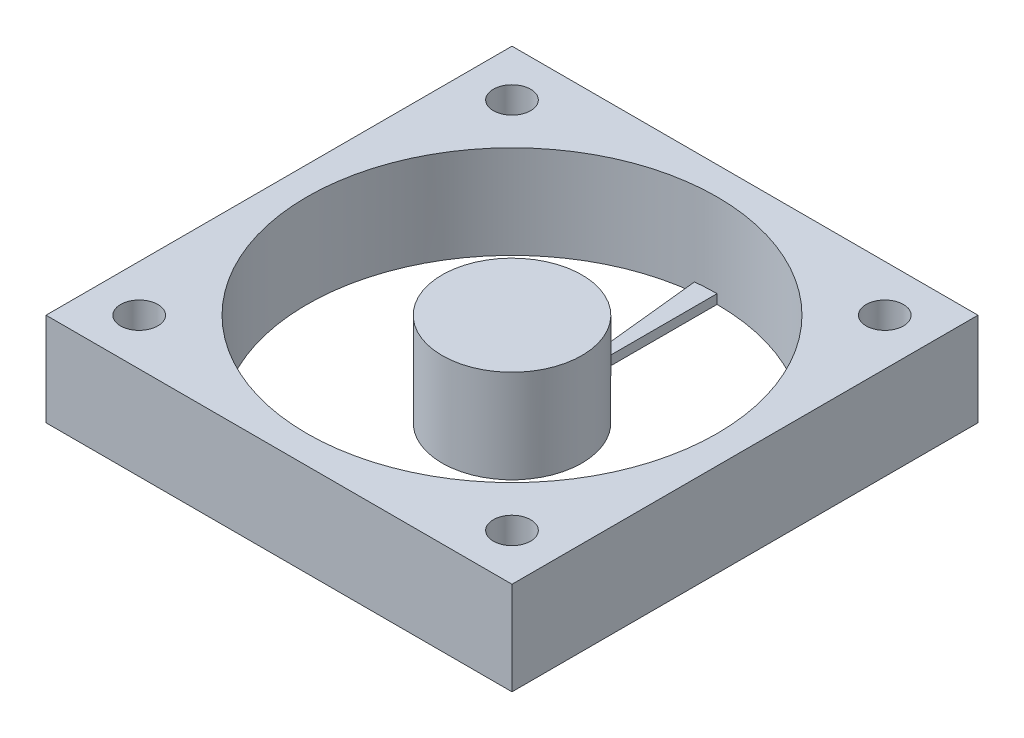
SolidWorks part; units mm, degrees
ref_plane "前视基准面" through (0, 0, 0) normal (0, 0, 1) x (1, 0, 0)
ref_plane "上视基准面" through (0, 0, 0) normal (0, 1, 0) x (1, 0, 0)
ref_plane "右视基准面" through (0, 0, 0) normal (1, 0, 0) x (0, 0, -1)
sketch "草图1" plane through (0, 0, 0) normal (0, 1, 0) x (1, 0, 0)
  line L0 (45, 5) -> (5, 45) construction
  line L1 (0, 0) -> (50, 0)
  line L2 (0, 0) -> (0, 50)
  line L3 (0, 50) -> (50, 50)
  line L4 (50, 0) -> (50, 50)
  line L5 (25, 25) -> (25, 50) construction
  line L6 (25, 25) -> (0, 25) construction
  circle A0 centre (5, 45) radius 2
  circle A1 centre (45, 45) radius 2
  circle A2 centre (45, 5) radius 2
  circle A3 centre (5, 5) radius 2
  point P15 (0, 0)
  dimension "D3" = 40
  dimension "D4" = 4
  dimension "D1" = 50
  dimension "D2" = 40
extrude "凸台-拉伸1" add sketch "草图1" along normal blind 10
sketch "草图2" plane through (0, 10, 0) normal (0, 1, 0) x (1, 0, 0)
  line L0 (25, 50) -> (25, 25) construction
  line L1 (50, 50) -> (0, 50) construction
  line L2 (25, 25) -> (0, 25) construction
  line L3 (0, 50) -> (0, 0) construction
  circle A0 centre (25, 25) radius 7.5
  circle A1 centre (25, 25) radius 22
  point P7 (0, 0)
  point P11 (25, 24.1234)
  dimension "D1" = 44
  dimension "D2" = 15
extrude "切除-拉伸2" cut sketch "草图2" against normal blind 9
sketch "草图3" plane through (0, 1, 0) normal (0, 1, 0) x (1, 0, 0)
  line L0 (24.216, 32.4589) -> (22.7004, 46.8795)
  line L1 (25, 32.5) -> (25, 47)
  circle A0 centre (25, 25) radius 7.5 construction
  circle A1 centre (25, 25) radius 7.5 construction
  arc A2 (25, 32.5) -> (24.216, 32.4589) centre (25, 25) cw
  arc A3 (22.7004, 46.8795) -> (25, 47) centre (25, 25) ccw
  circle A4 centre (25, 25) radius 22 construction
  dimension "D1" = 6
extrude "切除-拉伸3" cut sketch "草图3" along direction (0, -1, 0) on the side against the normal up to next (1 mm away)
